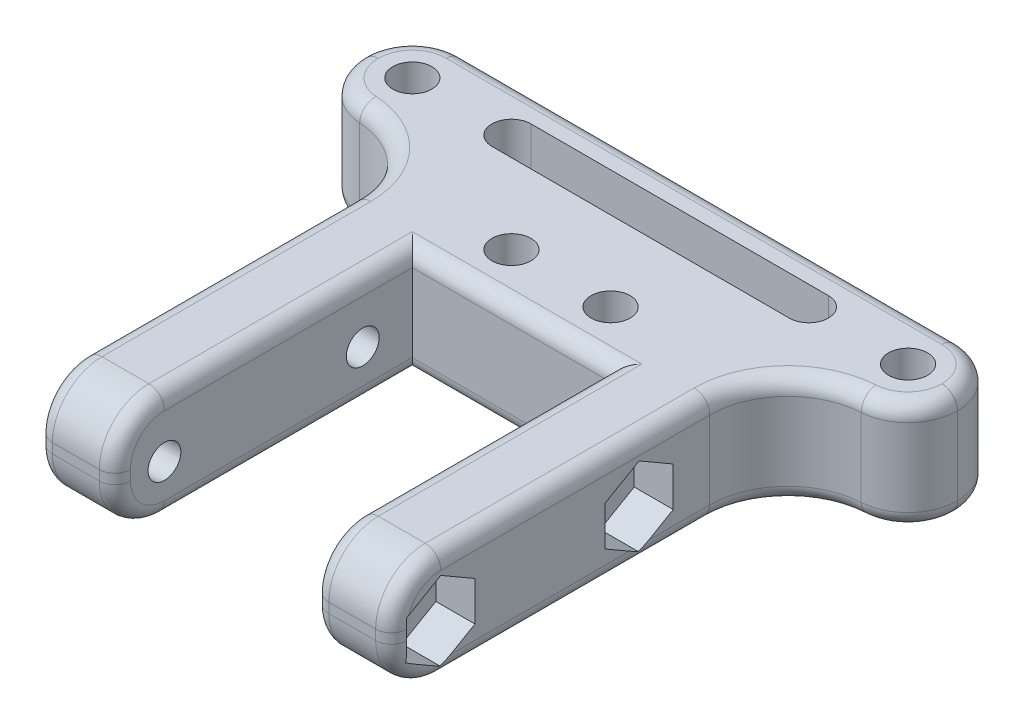
SolidWorks part; units mm, degrees
ref_plane "Front Plane" through (0, 0, 0) normal (0, 0, 1) x (1, 0, 0)
ref_plane "Top Plane" through (0, 0, 0) normal (0, 1, 0) x (1, 0, 0)
ref_plane "Right Plane" through (0, 0, 0) normal (1, 0, 0) x (0, 0, -1)
sketch "Sketch1" plane through (0, 0, 0) normal (0, 1, 0) x (1, 0, 0)
  line L0 (31.75, -6.35) -> (31.75, -37.8692) construction
  line L1 (-6.35, 6.35) -> (69.85, 6.35)
  line L2 (-6.35, 6.35) -> (-6.35, -6.35)
  line L3 (-6.35, -6.35) -> (-0.95, -6.35)
  line L4 (69.85, 6.35) -> (69.85, -6.35)
  line L6 (9.05, -16.35) -> (9.05, -57.15)
  line L7 (9.05, -57.15) -> (19.05, -57.15)
  line L11 (44.45, -57.15) -> (54.45, -57.15)
  line L12 (54.45, -16.35) -> (54.45, -57.15)
  line L13 (64.45, -6.35) -> (69.85, -6.35)
  line L14 (19.05, -57.15) -> (19.05, -19.05)
  line L15 (19.05, -19.05) -> (44.45, -19.05)
  line L16 (44.45, -19.05) -> (44.45, -57.15)
  line L17 (12.7, 0) -> (50.8, 0) construction
  line L18 (12.7, 2.5) -> (50.8, 2.5)
  line L19 (12.7, -2.5) -> (50.8, -2.5)
  circle A0 centre (0, 0) radius 2.5
  circle A1 centre (63.5, 0) radius 2.5
  arc A2 (9.05, -16.35) -> (-0.95, -6.35) centre (-0.95, -16.35) ccw
  arc A3 (54.45, -16.35) -> (64.45, -6.35) centre (64.45, -16.35) cw
  arc A4 (12.7, 2.5) -> (12.7, -2.5) centre (12.7, 0) ccw
  arc A5 (50.8, -2.5) -> (50.8, 2.5) centre (50.8, 0) ccw
  circle A6 centre (38.1, -12.7) radius 2.5
  circle A7 centre (25.4, -12.7) radius 2.5
  point P23 (54.45, -6.35)
  point P26 (31.75, 0)
  dimension "D1" = 5
  dimension "D10" = 10
  dimension "D16" = 2.5
  dimension "D2" = 63.5
  dimension "D3" = 6.35
  dimension "D4" = 6.35
  dimension "D5" = 12.7
  dimension "D6" = 6.35
  dimension "D7" = 25.4
  dimension "D8" = 10
  dimension "D9" = 10
  dimension "D11" = 50.8
  dimension "D13" = 6.35
  dimension "D14" = 50.8
  dimension "D15" = 38.1
  dimension "D17" = 12.7
  dimension "D18" = 12.7
  dimension "D19" = 6.35
extrude "Boss-Extrude2" add sketch "Sketch1" along normal blind 13.97
fillet "Fillet1" radius 6.35 4 edges at (49.45, 0, 57.15) (49.45, 13.97, 57.15) (14.05, 0, 57.15) (14.05, 13.97, 57.15)
fillet "Fillet2" radius 6.35 4 edges at (69.85, 6.985, 6.35) (69.85, 6.985, -6.35) (-6.35, 6.985, -6.35) (-6.35, 6.985, 6.35)
fillet "Fillet3" radius 2 28 edges at (-4.6187, 13.97, 4.3854) (-6.35, 13.97, 0.0138) (-4.4901, 13.97, -4.4901) (31.75, 13.97, -6.35) (67.9901, 13.97, -4.4901) (69.85, 13.97, 0.0138) (68.1187, 13.97, 4.3854) (57.1764, 13.97, 9.4874) (54.45, 13.97, 33.575) (54.45, 12.1101, 55.2901) (54.45, 1.8599, 55.2901) (54.45, 0, 33.575) (57.1764, 0, 9.4874) (68.1187, 0, 4.3854) (69.85, 0, 0.0138) (67.9901, 0, -4.4901) (31.75, 0, -6.35) (-4.4901, 0, -4.4901) (-6.35, 0, 0.0138) (-4.6187, 0, 4.3854) (6.3236, 0, 9.4874) (9.05, 0, 33.575) (9.05, 1.8599, 55.2901) (9.05, 12.1101, 55.2901) (9.05, 13.97, 33.575) (6.3236, 13.97, 9.4874) (54.45, 6.985, 57.15) (9.05, 6.985, 57.15)
sketch "Sketch2" plane through (9.05, 0, 0) normal (-1, 0, 0) x (0, 0, 1)
  line L0 (50.8, 11.97) -> (50.8, 13.97) construction
  line L2 (58.1369, 6.35) -> (54.6755, 6.35) construction
  line L6 (16.35, 13.97) -> (50.8, 13.97)
  circle A0 centre (50.8, 6.35) radius 2.1
  circle A1 centre (25.4, 6.35) radius 2.1
  circle A2 centre (25.4, 6.35) radius 4.25
  point P7 (50.8, 12.97)
  dimension "D1" = 4.2
  dimension "D2" = 4.2
  dimension "D4" = 8.5
  dimension "D3" = 25.4
  dimension "D5" = 7.62
extrude "Cut-Extrude1" cut sketch "Sketch2" against normal up to surface (45.4 mm away) contours A0 | A1 | L2 A1 | L2 A0
sketch "Sketch3" plane through (54.45, 0, 0) normal (1, 0, 0) x (0, 0, -1)
  line L1 (-25.4, 1.2982) -> (-21.025, 3.8241)
  line L2 (-21.025, 3.8241) -> (-21.025, 8.8759)
  line L3 (-21.025, 8.8759) -> (-25.4, 11.4018)
  line L4 (-25.4, 11.4018) -> (-29.775, 8.8759)
  line L5 (-29.775, 8.8759) -> (-29.775, 3.8241)
  line L6 (-29.775, 3.8241) -> (-25.4, 1.2982)
  line L7 (-50.8, 1.2982) -> (-46.425, 3.8241)
  line L8 (-46.425, 3.8241) -> (-46.425, 8.8759)
  line L9 (-46.425, 8.8759) -> (-50.8, 11.4018)
  line L10 (-50.8, 11.4018) -> (-55.175, 8.8759)
  line L11 (-55.175, 8.8759) -> (-55.175, 3.8241)
  line L12 (-55.175, 3.8241) -> (-50.8, 1.2982)
  circle A0 centre (-25.4, 6.35) radius 4.375 construction
  circle A1 centre (-50.8, 6.35) radius 4.375 construction
  dimension "D1" = 8.75
  dimension "D2" = 8.75
extrude "Cut-Extrude4" cut sketch "Sketch3" against normal blind 5 and the other way blind 12.7
fillet "Fillet4" radius 2 12 edges at (19.05, 0, 34.925) (19.05, 1.8599, 55.2901) (19.05, 12.1101, 55.2901) (44.45, 0, 34.925) (44.45, 1.8599, 55.2901) (44.45, 12.1101, 55.2901) (19.05, 13.97, 34.925) (31.75, 0, 19.05) (31.75, 13.97, 19.05) (44.45, 13.97, 34.925) (19.05, 6.985, 57.15) (44.45, 6.985, 57.15)
